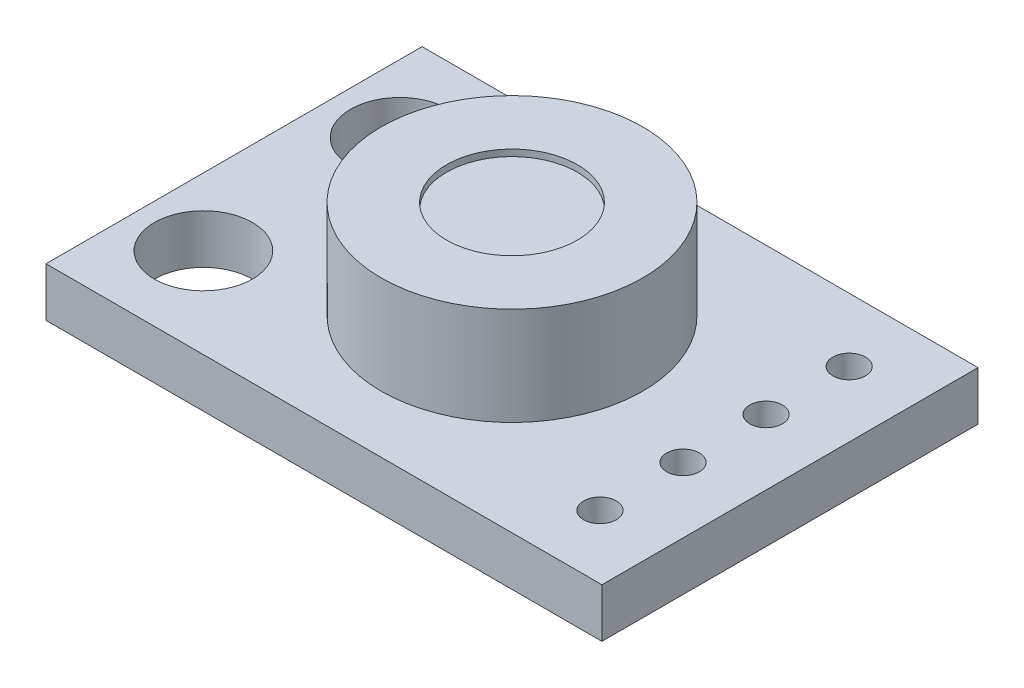
SolidWorks part; units mm, degrees
ref_plane "Спереди" through (0, 0, 0) normal (0, 0, 1) x (1, 0, 0)
ref_plane "Сверху" through (0, 0, 0) normal (0, 1, 0) x (1, 0, 0)
ref_plane "Справа" through (0, 0, 0) normal (1, 0, 0) x (0, 0, -1)
sketch "Эскиз1" plane through (0, 0, 0) normal (0, 1, 0) x (1, 0, 0)
  line L1 (-8.5, 5.75) -> (8.5, 5.75)
  line L2 (-8.5, 5.75) -> (-8.5, -5.75)
  line L3 (-8.5, -5.75) -> (8.5, -5.75)
  line L4 (8.5, 5.75) -> (8.5, -5.75)
  line L5 (-8.5, 5.75) -> (8.5, -5.75) construction
  line L6 (-8.5, -5.75) -> (8.5, 5.75) construction
  point P0 (0, 0)
  dimension "D1" = 17
  dimension "D2" = 11.5
extrude "Бобышка-Вытянуть1" add sketch "Эскиз1" along normal blind 1.5
sketch "Эскиз2" plane through (0, 1.5, 0) normal (0, 1, 0) x (1, 0, 0)
  circle A0 centre (0, 0) radius 4
  dimension "D1" = 8
extrude "Бобышка-Вытянуть2" add sketch "Эскиз2" along normal blind 3
sketch "Эскиз3" plane through (0, 4.5, 0) normal (0, 1, 0) x (1, 0, 0)
  circle A0 centre (0, 0) radius 2
  dimension "D1" = 4
extrude "Вырез-Вытянуть1" cut sketch "Эскиз3" against normal blind 0.2
sketch "Эскиз4" plane through (0, 1.5, 0) normal (0, 1, 0) x (1, 0, 0)
  line L0 (-8.5, 0) -> (8.5, 0) construction
  line L1 (-8.5, 5.75) -> (-8.5, -5.75) construction
  line L2 (8.5, -5.75) -> (8.5, 5.75) construction
  line L3 (6.5, 5.75) -> (6.5, -5.75) construction
  line L4 (8.5, 5.75) -> (-8.5, 5.75) construction
  line L5 (-8.5, -5.75) -> (8.5, -5.75) construction
  line L6 (6.5, 3.81) -> (6.5, 5.75) construction
  line L7 (6.5, -3.81) -> (6.5, -5.75) construction
  line L8 (6.5, -1.27) -> (6.5, 1.27) construction
  line L9 (-6.4373, 3) -> (-6.4373, -5.0353) construction
  circle A0 centre (6.5, 3.81) radius 0.5
  circle A1 centre (6.5, 1.27) radius 0.5
  circle A2 centre (6.5, -1.27) radius 0.5
  circle A3 centre (6.5, -3.81) radius 0.5
  circle A4 centre (-6.4373, 3) radius 1.5
  circle A5 centre (-6.4373, -3) radius 1.5
  point P14 (6.5, 0)
  dimension "D2" = 1
  dimension "D4" = 6
  dimension "D5" = 2.54
  dimension "D6" = 3
  dimension "D1" = 2
  dimension "D3" = 4
extrude "Вырез-Вытянуть2" cut sketch "Эскиз4" against normal through all
